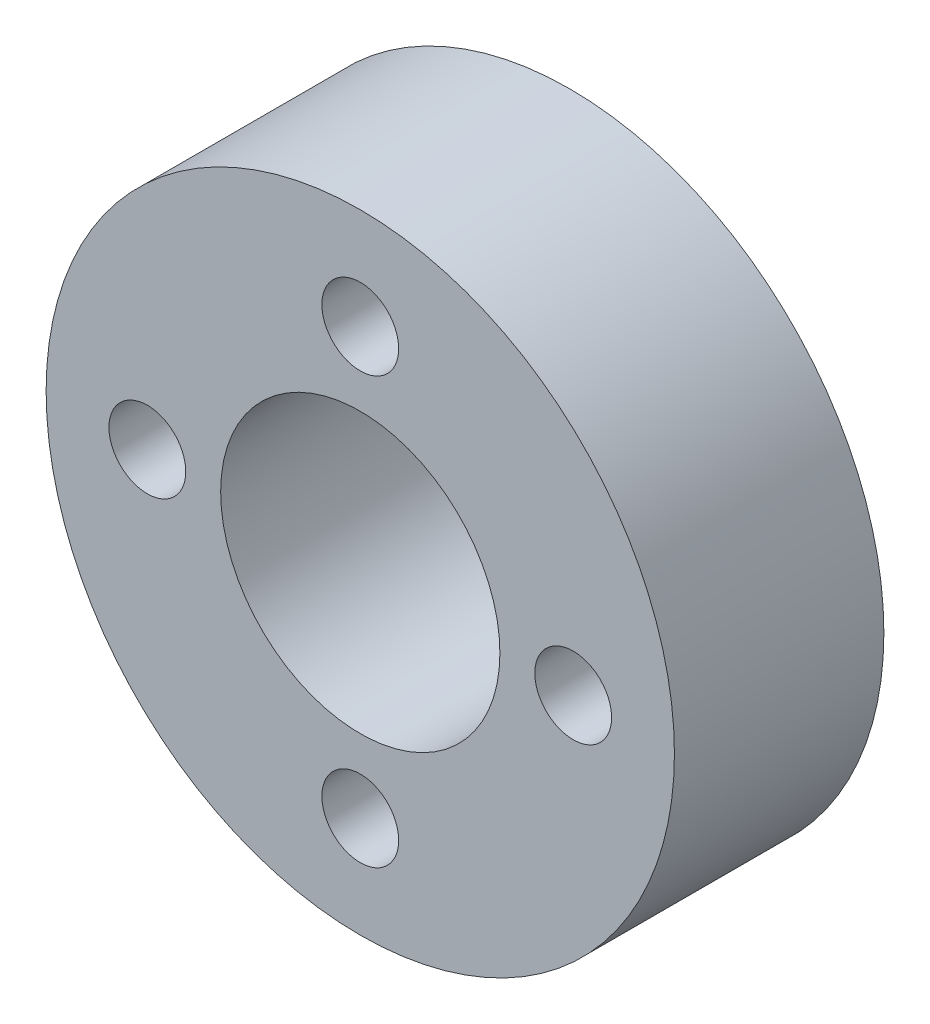
SolidWorks part; units mm, degrees
ref_plane "Ebene vorne" through (0, 0, 0) normal (0, 0, 1) x (1, 0, 0)
ref_plane "Ebene oben" through (0, 0, 0) normal (0, 1, 0) x (1, 0, 0)
ref_plane "Ebene rechts" through (0, 0, 0) normal (1, 0, 0) x (0, 0, -1)
sketch "Skizze1" plane through (0, 0, 0) normal (0, 0, 1) x (1, 0, 0)
  circle A0 centre (0, 0) radius 22.5
  dimension "D1" = 45
extrude "Aufsatz-Linear austragen1" add sketch "Skizze1" along normal blind 15 contours A0
sketch "Skizze2" plane through (0, 0, 0) normal (0, 0, -1) x (-1, 0, 0)
  circle A0 centre (0, 0) radius 16
  dimension "D1" = 32
extrude "Aufsatz-Linear austragen2" add sketch "Skizze2" along normal blind 2
sketch "Skizze3" plane through (0, 0, -2) normal (0, 0, -1) x (-1, 0, 0)
  circle A0 centre (0, 0) radius 10
  dimension "D1" = 20
extrude "Schnitt-Linear austragen1" cut sketch "Skizze3" against normal through all
sketch "Skizze7" plane through (0, 0, -2) normal (0, 0, -1) x (-1, 0, 0)
  circle A0 centre (0, 0) radius 15.25 construction
  circle A1 centre (0, 15.25) radius 2.75
  circle A2 centre (15.25, 0) radius 2.75
  circle A3 centre (0, -15.25) radius 2.75
  circle A4 centre (-15.25, 0) radius 2.75
  dimension "D1" = 30.5
  dimension "D2" = 5.5
  dimension "D3" = 4
extrude "Schnitt-Linear austragen2" cut sketch "Skizze7" against normal through all contours A1 | A4 | A2 | A3
